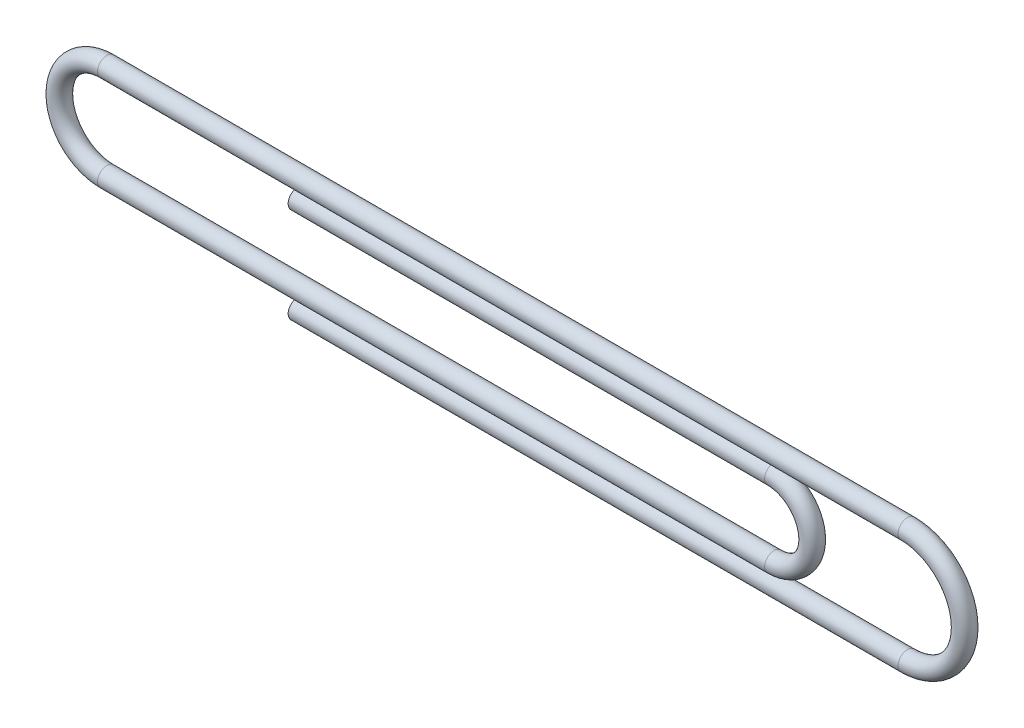
SolidWorks part; units mm, degrees
ref_plane "Front Plane" through (0, 0, 0) normal (0, 0, 1) x (1, 0, 0)
ref_plane "Top Plane" through (0, 0, 0) normal (0, 1, 0) x (1, 0, 0)
ref_plane "Right Plane" through (0, 0, 0) normal (1, 0, 0) x (0, 0, -1)
sketch "Sketch1" plane through (0, 0, 0) normal (0, 0, 1) x (1, 0, 0)
  line L0 (16.6547, 2.1115) -> (-8.3453, 2.1115)
  line L2 (16.6547, -1.8885) -> (-18.3453, -1.8885)
  line L4 (-18.3453, 3.1115) -> (23.6547, 3.1115)
  line L6 (23.6547, -2.8885) -> (-8.3453, -2.8885)
  arc A0 (16.6547, -1.8885) -> (16.6547, 2.1115) centre (16.6547, 0.1115) ccw
  arc A1 (23.6547, -2.8885) -> (23.6547, 3.1115) centre (23.6547, 0.1115) ccw
  arc A2 (-18.3453, 3.1115) -> (-18.3453, -1.8885) centre (-18.3453, 0.6115) ccw
  dimension "D1" = 25
  dimension "D2" = 35
  dimension "D3" = 42
  dimension "D4" = 1
  dimension "D5" = 1
  dimension "D6" = 4
  dimension "D7" = 32
sweep "Sweep1" add path "Sketch1" circular profile diameter 0.99 parameters "D3"=0.99
